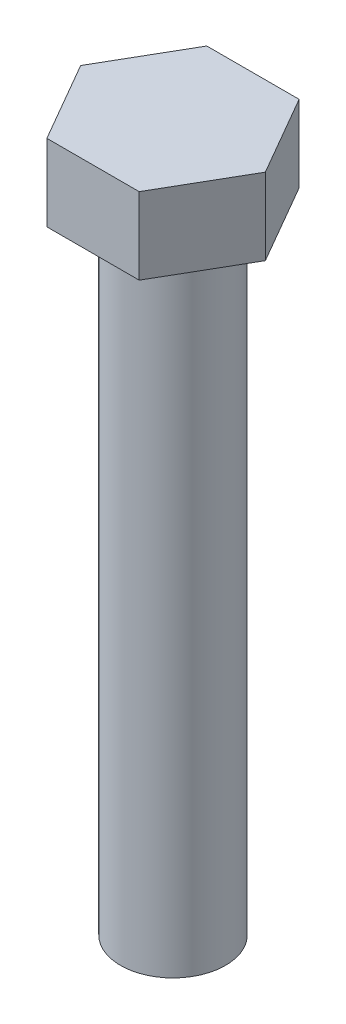
SolidWorks part; units mm, degrees
ref_plane "Front Plane" through (0, 0, 0) normal (0, 0, 1) x (1, 0, 0)
ref_plane "Top Plane" through (0, 0, 0) normal (0, 1, 0) x (1, 0, 0)
ref_plane "Right Plane" through (0, 0, 0) normal (1, 0, 0) x (0, 0, -1)
sketch "Sketch1" plane through (0, 0, 0) normal (0, 1, 0) x (1, 0, 0)
  line L1 (2.1975, -3.8062) -> (4.395, 0)
  line L2 (4.395, 0) -> (2.1975, 3.8062)
  line L3 (2.1975, 3.8062) -> (-2.1975, 3.8062)
  line L4 (-2.1975, 3.8062) -> (-4.395, 0)
  line L5 (-4.395, 0) -> (-2.1975, -3.8062)
  line L6 (-2.1975, -3.8062) -> (2.1975, -3.8062)
  circle A0 centre (0, 0) radius 3.8062 construction
  dimension "D1" = 8.79
extrude "Boss-Extrude1" add sketch "Sketch1" along normal blind 3.65
sketch "Sketch2" plane through (0, 0, 0) normal (0, -1, 0) x (1, 0, 0)
  circle A0 centre (0, 0) radius 2.5
  dimension "D1" = 5
extrude "Boss-Extrude2" add sketch "Sketch2" along normal blind 30
